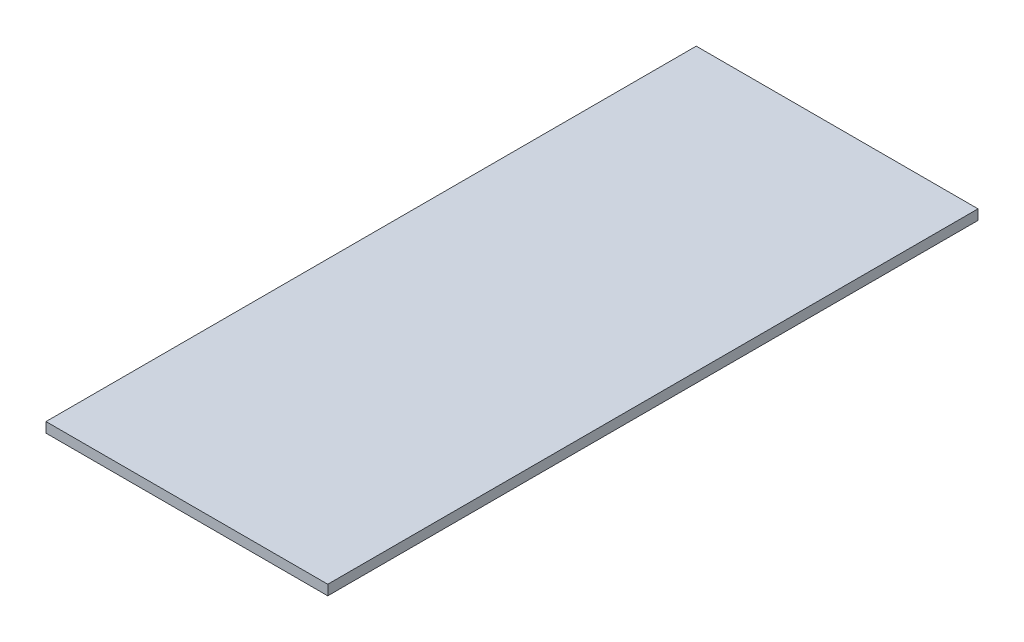
SolidWorks part; units mm, degrees
ref_plane "Front Plane" through (0, 0, 0) normal (0, 0, 1) x (1, 0, 0)
ref_plane "Top Plane" through (0, 0, 0) normal (0, 1, 0) x (1, 0, 0)
ref_plane "Right Plane" through (0, 0, 0) normal (1, 0, 0) x (0, 0, -1)
sketch "Sketch1" plane through (0, 0, 0) normal (0, 1, 0) x (1, 0, 0)
  line L1 (0, 0) -> (66.04, 0)
  line L2 (0, 0) -> (0, 152.4)
  line L3 (0, 152.4) -> (66.04, 152.4)
  line L4 (66.04, 0) -> (66.04, 152.4)
  dimension "D1" = 66.04
  dimension "D2" = 152.4
extrude "Boss-Extrude1" add sketch "Sketch1" along normal blind 2.3622
